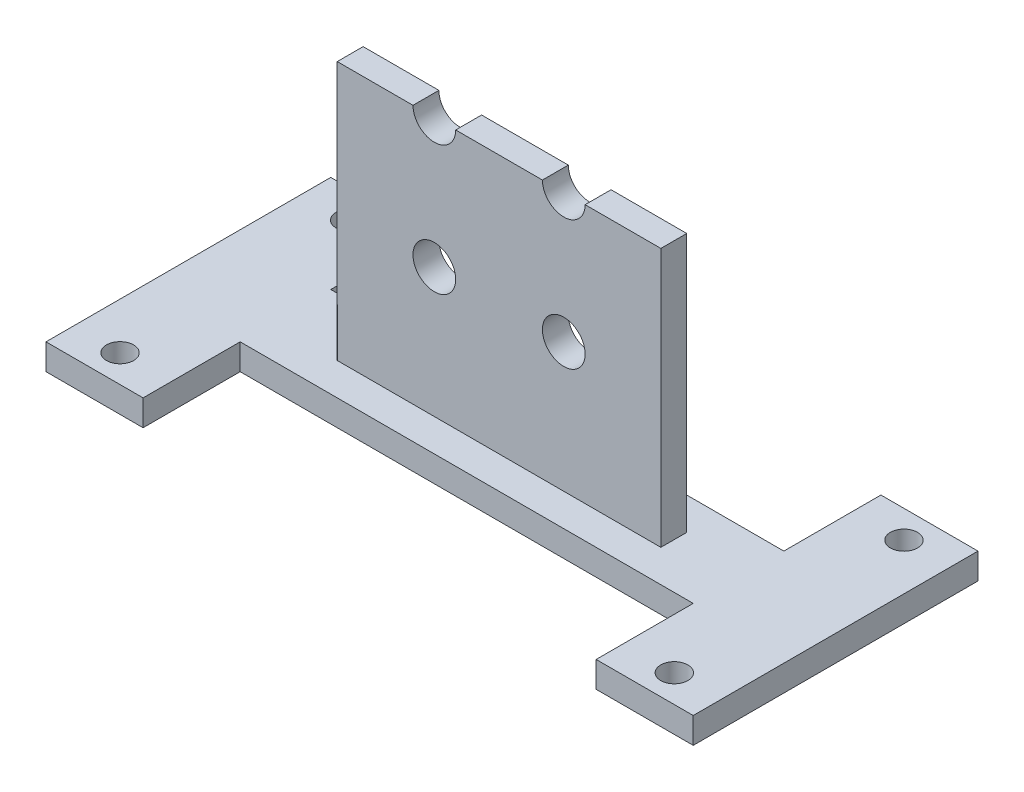
SolidWorks part; units mm, degrees
ref_plane "前视基准面" through (0, 0, 0) normal (0, 0, 1) x (1, 0, 0)
ref_plane "上视基准面" through (0, 0, 0) normal (0, 1, 0) x (1, 0, 0)
ref_plane "右视基准面" through (0, 0, 0) normal (1, 0, 0) x (0, 0, -1)
sketch "草图1" plane through (0, 0, 0) normal (0, 1, 0) x (1, 0, 0)
  line L0 (-55, 0) -> (55, 0) construction
  line L1 (-25, -11) -> (25, -11)
  line L2 (-25, -11) -> (-25, 11)
  line L3 (-25, 11) -> (25, 11)
  line L4 (25, -11) -> (25, 11)
  line L5 (-25, -11) -> (25, 11) construction
  line L6 (-25, 11) -> (25, -11) construction
  line L7 (0, -55) -> (0, 55) construction
  circle A0 centre (-21.41, 8.87) radius 1.05
  circle A1 centre (-21.41, -8.87) radius 1.05
  circle A2 centre (21.41, -8.87) radius 1.05
  circle A3 centre (21.41, 8.87) radius 1.05
  point P0 (0, 0)
  point P18 (-15, 8.87)
  dimension "D2" = 17.74
  dimension "D3" = 42.82
  dimension "D5" = 2.1
  dimension "D1" = 50
  dimension "D4" = 22
extrude "凸台-拉伸1" add sketch "草图1" along normal blind 2
sketch "草图2" plane through (0, 2, 0) normal (0, 1, 0) x (1, 0, 0)
  line L1 (-12.5, -1) -> (12.5, -1)
  line L2 (-12.5, -1) -> (-12.5, 1)
  line L3 (-12.5, 1) -> (12.5, 1)
  line L4 (12.5, -1) -> (12.5, 1)
  line L5 (-12.5, -1) -> (12.5, 1) construction
  line L6 (-12.5, 1) -> (12.5, -1) construction
  point P0 (0, 0)
  dimension "D1" = 2
  dimension "D2" = 25
extrude "凸台-拉伸2" add sketch "草图2" along normal blind 20
sketch "草图3" plane through (0, 0, 1) normal (0, 0, 1) x (1, 0, 0)
  line L0 (0, -1.1) -> (0, 1.1) construction
  line L1 (-12.5, 2) -> (12.5, 2) construction
  circle A0 centre (-5, 22) radius 1.65
  circle A1 centre (-5, 12) radius 1.65
  circle A2 centre (5, 12) radius 1.65
  circle A3 centre (5, 22) radius 1.65
  dimension "D1" = 3.3
  dimension "D2" = 3.3
  dimension "D3" = 10
  dimension "D4" = 10
  dimension "D5" = 10
extrude "切除-拉伸1" cut sketch "草图3" against normal blind 30
sketch "草图4" plane through (0, 2, 0) normal (0, 1, 0) x (1, 0, 0)
  line L0 (-25, -11) -> (25, -11) construction
  line L1 (-17.5, -18.5) -> (17.5, -18.5)
  line L2 (-17.5, -18.5) -> (-17.5, -3.5)
  line L3 (-17.5, -3.5) -> (17.5, -3.5)
  line L4 (17.5, -18.5) -> (17.5, -3.5)
  line L5 (-17.5, -18.5) -> (17.5, -3.5) construction
  line L6 (-17.5, -3.5) -> (17.5, -18.5) construction
  line L7 (-1.1, 0) -> (1.1, 0) construction
  line L8 (-17.5, 3.5) -> (17.5, 18.5) construction
  line L9 (-17.5, 18.5) -> (17.5, 3.5) construction
  line L10 (17.5, 18.5) -> (17.5, 3.5)
  line L11 (-17.5, 3.5) -> (17.5, 3.5)
  line L12 (-17.5, 18.5) -> (-17.5, 3.5)
  line L13 (-17.5, 18.5) -> (17.5, 18.5)
  point P0 (0, -11)
  point P13 (0, 11)
  dimension "D1" = 7.5
  dimension "D2" = 35
extrude "切除-拉伸2" cut sketch "草图4" against normal blind 30
